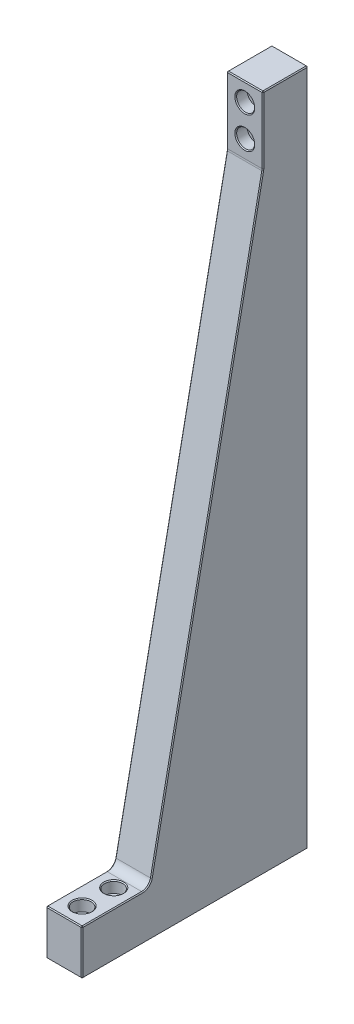
SolidWorks part; units mm, degrees
material "Plain Carbon Steel"
ref_plane "Front Plane" through (0, 0, 0) normal (0, 0, 1) x (1, 0, 0)
ref_plane "Top Plane" through (0, 0, 0) normal (0, 1, 0) x (1, 0, 0)
ref_plane "Right Plane" through (0, 0, 0) normal (1, 0, 0) x (0, 0, -1)
sketch "Sketch1" plane through (0, 0, 0) normal (1, 0, 0) x (0, 0, -1)
  line L0 (0, 0) -> (250, 0)
  line L1 (250, 0) -> (250, 750)
  line L2 (250, 750) -> (200, 750)
  line L3 (200, 750) -> (200, 675)
  line L4 (200, 675) -> (75, 50)
  line L5 (75, 50) -> (0, 50)
  line L6 (0, 50) -> (0, 0)
  dimension "D1" = 750
  dimension "D2" = 250
  dimension "D3" = 75
  dimension "D4" = 50
  dimension "D5" = 50
extrude "Boss-Extrude1" add sketch "Sketch1" along normal mid plane 40
hole_wizard "CBORE for M12 Hex Socket Head Cap Screw1" positions "Sketch4" profile "Sketch3" counterbore size "M12" standard "ISO" end condition through all
sketch "Sketch4" plane through (0, 50, 0) normal (0, 1, 0) x (1, 0, 0)
  line L0 (20, 37.5) -> (-20, 37.5) construction
  line L1 (20, 75) -> (20, 0) construction
  line L2 (-20, 75) -> (-20, 0) construction
  point P1 (0, 55)
  point P3 (0, 20)
  dimension "D1" = 35
sketch "Sketch3" plane through (0, 50, -55) normal (1, 0, 0) x (0, 0, 1)
  line L0 (0, 0) -> (0, 50)
  line L1 (0, 50) -> (6.75, 50)
  line L3 (6.75, 50) -> (6.75, 12.6)
  line L4 (6.75, 12.6) -> (10, 12.6)
  line L5 (10, 12.6) -> (10, 0)
  line L7 (10, 0) -> (0, 0)
  line L11 (0, -6.35) -> (0, 107.95) construction
  dimension "Thru Hole Dia." = 13.5
  dimension "Thru Hole Depth" = 50
  dimension "C'Bore Dia." = 20
  dimension "C'Bore Depth" = 12.6
hole_wizard "CBORE for M12 Hex Socket Head Cap Screw2" positions "Sketch7" profile "Sketch6" counterbore size "M12" standard "ISO" end condition through all
sketch "Sketch7" plane through (0, 0, -200) normal (0, 0, 1) x (1, 0, 0)
  line L0 (20, 712.5) -> (-20, 712.5) construction
  line L1 (20, 750) -> (20, 675) construction
  line L2 (-20, 750) -> (-20, 675) construction
  point P0 (0, 730)
  point P2 (0, 695)
  dimension "D1" = 35
sketch "Sketch6" plane through (0, 730, -200) normal (1, 0, 0) x (0, -1, 0)
  line L0 (0, 0) -> (0, 50)
  line L1 (0, 50) -> (6.75, 50)
  line L3 (6.75, 50) -> (6.75, 12.6)
  line L4 (6.75, 12.6) -> (10, 12.6)
  line L5 (10, 12.6) -> (10, 0)
  line L7 (10, 0) -> (0, 0)
  line L11 (0, -6.35) -> (0, 107.95) construction
  dimension "Thru Hole Dia." = 13.5
  dimension "Thru Hole Depth" = 50
  dimension "C'Bore Dia." = 20
  dimension "C'Bore Depth" = 12.6
fillet "Fillet1" radius 10 2 edges at (0, 50, -75) (0, 675, -200)
chamfer "Chamfer1" distance 1 angle 45 27 edges at (0, 0, -13.25) (0, 0, -48.25) (6.75, 695, -250) (6.75, 730, -250) (0, 750, -200) (0, 50, 0) (0, 0, 0) (-20, 0, -125) (-20, 25, 0) (-20, 50, -33.401) (-20, 52.2666, -73.1419) (-20, 366.0339, -138.2068) (-20, 675.0048, -199.9513) (-20, 712.9951, -200) (-20, 750, -225) (0, 0, -250) (-20, 375, -250) (0, 750, -250) (20, 50, -33.401) (20, 52.2666, -73.1419) (20, 366.0339, -138.2068) (20, 675.0048, -199.9513) (20, 712.9951, -200) (20, 750, -225) (20, 375, -250) (20, 0, -125) (20, 25, 0)
chamfer "Chamfer2" distance 1 angle 45 4 edges at (0, 50, -10) (0, 50, -45) (10, 695, -200) (10, 730, -200)
